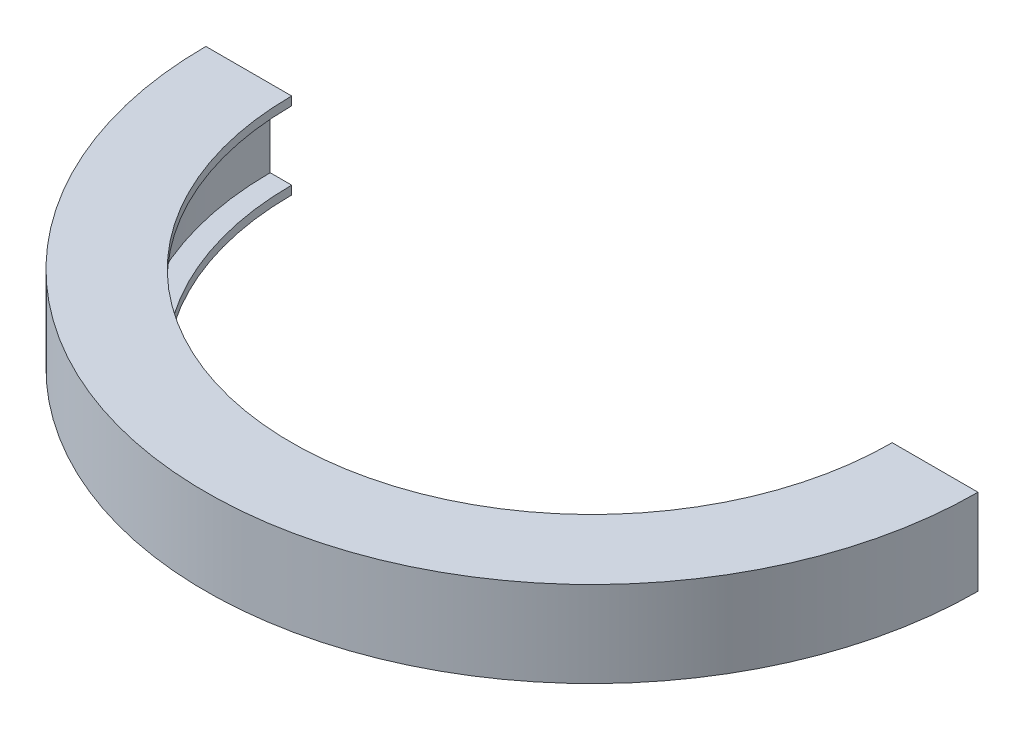
SolidWorks part; units mm, degrees
material "Nylon 6/10"
ref_plane "Front Plane" through (0, 0, 0) normal (0, 0, 1) x (1, 0, 0)
ref_plane "Top Plane" through (0, 0, 0) normal (0, 1, 0) x (1, 0, 0)
ref_plane "Right Plane" through (0, 0, 0) normal (1, 0, 0) x (0, 0, -1)
sketch "Sketch1" plane through (0, 0, 0) normal (0, 1, 0) x (1, 0, 0)
  line L4 (-90, 0) -> (90, 0)
  arc A0 (-70, 0) -> (70, 0) centre (0, 0) ccw
  arc A1 (-90, 0) -> (90, 0) centre (0, 0) ccw
  point P1 (0, 0)
  dimension "D1" = 70
  dimension "D2" = 180
extrude "Boss-Extrude1" add sketch "Sketch1" along normal mid plane 20
ref_axis "Axis1" through (0, 5.6359, 0) along (0, -1, 0)
sketch "Sketch2" plane through (0, 0, 0) normal (0, 0, -1) x (-1, 0, 0)
  line L1 (70, -8) -> (75, -8)
  line L2 (70, -8) -> (70, 8)
  line L3 (70, 8) -> (75, 8)
  line L4 (75, -8) -> (75, 8)
  line L5 (70, 10) -> (70, -10) construction
  line L6 (90, -10) -> (70, -10) construction
  line L7 (90, 10) -> (70, 10) construction
  line L8 (90, 10) -> (90, -10) construction
  dimension "D1" = 15
  dimension "D2" = 2
  dimension "D3" = 2
revolve "Cut-Revolve1" cut sketch "Sketch2" angle 360 about axis through (0, 5.6359, 0) along (0, -1, 0)
